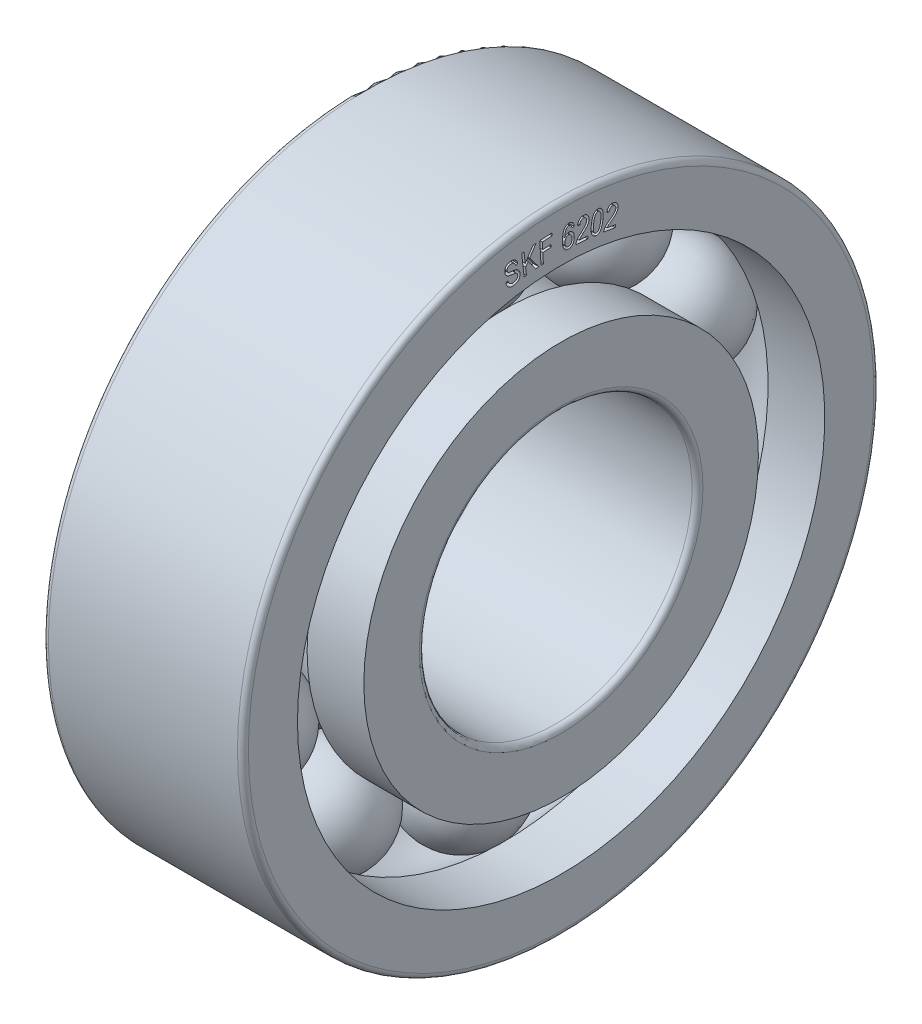
SolidWorks part; units mm, degrees
ref_plane "Alzado" through (0, 0, 0) normal (0, 0, 1) x (1, 0, 0)
ref_plane "Planta" through (0, 0, 0) normal (0, 1, 0) x (1, 0, 0)
ref_plane "Vista lateral" through (0, 0, 0) normal (1, 0, 0) x (0, 0, -1)
sketch "Sketch1" plane through (0, 0, 0) normal (0, 0, 1) x (1, 0, 0)
  line L0 (0, 0) -> (29.9021, 0) construction
  line L1 (0, 14.5) -> (3.119, 14.5)
  line L2 (0, 17.5) -> (11, 17.5)
  line L3 (0, 17.5) -> (0, 14.5)
  line L4 (0, 7.5) -> (11, 7.5)
  line L5 (11, 17.5) -> (11, 14.5)
  line L6 (0, 10.85) -> (3.119, 10.85)
  line L7 (0, 10.85) -> (0, 7.5)
  line L8 (11, 10.85) -> (11, 7.5)
  line L9 (0, 14.5) -> (0, 10.85) construction
  line L10 (0, 12.675) -> (11, 12.675) construction
  line L11 (7.881, 10.85) -> (11, 10.85)
  line L12 (7.881, 14.5) -> (11, 14.5)
  arc A0 (3.119, 10.85) -> (7.881, 10.85) centre (5.5, 12.675) ccw
  arc A1 (7.881, 14.5) -> (3.119, 14.5) centre (5.5, 12.675) ccw
  dimension "D6" = 6
  dimension "D1" = 11
  dimension "D2" = 7.5
  dimension "D3" = 17.5
  dimension "D4" = 14.5
  dimension "D5" = 10.85
revolve "Revolve1" add sketch "Sketch1" angle 360 about L0
fillet "Fillet1" radius 0.3 2 edges at (0, 0, 17.5) (11, 0, 17.5)
fillet "Fillet2" radius 0.3 2 edges at (0, 0, 7.5) (11, 0, 7.5)
sketch "Sketch2" plane through (0, 0, 0) normal (0, 0, 1) x (1, 0, 0)
  line L0 (5.5, 15.675) -> (5.5, 9.675)
  arc A0 (5.5, 15.675) -> (5.5, 9.675) centre (5.5, 12.675) ccw
  arc A1 (7.881, 14.5) -> (3.119, 14.5) centre (5.5, 12.675) ccw construction
revolve "Revolve2" add sketch "Sketch2" angle 360 about L0
pattern_circular "CirPattern2" count 10 over 360 about axis through (0, 0, 0) along (1, 0, 0) of bodies 103
sketch "Sketch4" plane through (11, 0, 0) normal (1, 0, 0) x (0, 0, -1)
  arc A0 (-5.1432, 14.1971) -> (5.1432, 14.1971) centre (0, 0) cw construction
  circle A1 centre (0, 0) radius 14.5 construction
  text T0 "SKF 6202\r\n" font "Arial Narrow" height 1.2
  dimension "D1" = 0.6
extrude "Cut-Extrude1" cut sketch "Sketch4" against normal blind 0.3
